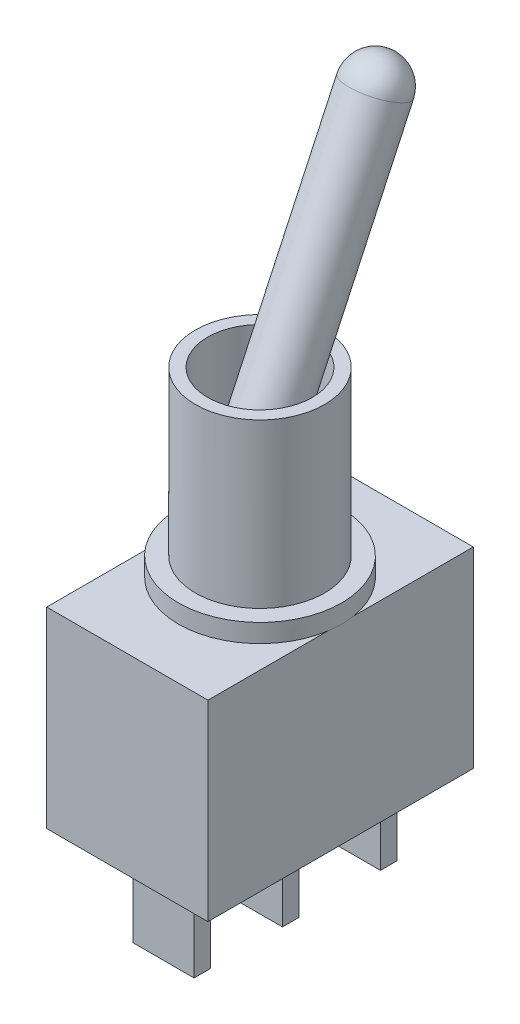
SolidWorks part; units mm, degrees
ref_plane "Front Plane" through (0, 0, 0) normal (0, 0, 1) x (1, 0, 0)
ref_plane "Top Plane" through (0, 0, 0) normal (0, 1, 0) x (1, 0, 0)
ref_plane "Right Plane" through (0, 0, 0) normal (1, 0, 0) x (0, 0, -1)
sketch "Sketch1" plane through (0, 0, 0) normal (0, 1, 0) x (1, 0, 0)
  circle A0 centre (0, 0) radius 3.1636
  circle A1 centre (0, 0) radius 2.5636
  dimension "D1" = 6.3271
  dimension "D2" = 0.6
extrude "Boss-Extrude1" add sketch "Sketch1" along normal blind 8
sketch "Sketch2" plane through (0, 0, 0) normal (0, -1, 0) x (1, 0, 0)
  circle A0 centre (0, 0) radius 4
  dimension "D1" = 8
extrude "Boss-Extrude2" add sketch "Sketch2" along normal blind 0.9
sketch "Sketch3" plane through (0, -0.9, 0) normal (0, -1, 0) x (1, 0, 0)
  line L1 (3.95, 6.5) -> (-3.95, 6.5)
  line L2 (3.95, 6.5) -> (3.95, -6.5)
  line L3 (3.95, -6.5) -> (-3.95, -6.5)
  line L4 (-3.95, 6.5) -> (-3.95, -6.5)
  line L5 (3.95, 6.5) -> (-3.95, -6.5) construction
  line L6 (3.95, -6.5) -> (-3.95, 6.5) construction
  point P0 (0, 0)
  dimension "D1" = 7.9
  dimension "D2" = 13
extrude "Boss-Extrude3" add sketch "Sketch3" along normal blind 9.4
sketch "Sketch4" plane through (0, -10.3, 0) normal (0, -1, 0) x (1, 0, 0)
  line L1 (-1.5, 4.7304) -> (1.5, 4.7304)
  line L2 (-1.5, 4.7304) -> (-1.5, 3.9304)
  line L3 (-1.5, 3.9304) -> (1.5, 3.9304)
  line L4 (1.5, 4.7304) -> (1.5, 3.9304)
  line L5 (-1.5, 4.7304) -> (1.5, 3.9304) construction
  line L6 (-1.5, 3.9304) -> (1.5, 4.7304) construction
  line L7 (-1.5, 0.4) -> (1.5, 0.4)
  line L8 (-1.5, 0.4) -> (-1.5, -0.4)
  line L9 (-1.5, -0.4) -> (1.5, -0.4)
  line L10 (1.5, 0.4) -> (1.5, -0.4)
  line L11 (-1.5, 0.4) -> (1.5, -0.4) construction
  line L12 (-1.5, -0.4) -> (1.5, 0.4) construction
  line L13 (-1.5, -4.4018) -> (1.5, -4.4018)
  line L14 (-1.5, -4.4018) -> (-1.5, -5.2018)
  line L15 (-1.5, -5.2018) -> (1.5, -5.2018)
  line L16 (1.5, -4.4018) -> (1.5, -5.2018)
  line L17 (-1.5, -4.4018) -> (1.5, -5.2018) construction
  line L18 (-1.5, -5.2018) -> (1.5, -4.4018) construction
  point P0 (0, 4.3304)
  point P5 (0, 0)
  point P11 (0, -4.8018)
  dimension "D1" = 0.8
  dimension "D2" = 3
extrude "Boss-Extrude4" add sketch "Sketch4" along normal blind 4.5
sketch "Sketch5" plane through (0, 0, 0) normal (1, 0, 0) x (0, 0, -1)
  line L0 (0, 15.1764) -> (0, -19.8038) construction
  line L1 (4.9222, 15.5556) -> (-7.7236, -11.5634) construction
  line L2 (4.3735, 17.6917) -> (-1.5207, 5.0515)
  line L3 (-1.5207, 5.0515) -> (-0.2519, 4.4599)
  line L4 (6.234, 18.3688) -> (5.8344, 18.5551) construction
  line L5 (3.1636, 8) -> (-3.1636, 8) construction
  line L6 (6.234, 18.3688) -> (-0.2519, 4.4599)
  arc A0 (4.3735, 17.6917) -> (6.234, 18.3688) centre (5.6423, 17.1) cw
  point P9 (-0.2519, 4.4599)
  point P14 (0, 5)
  dimension "D1" = 25
  dimension "D2" = 2.8
  dimension "D3" = 10.5
  dimension "D4" = 3
revolve "Revolve1" add sketch "Sketch5" angle 360 about L1
